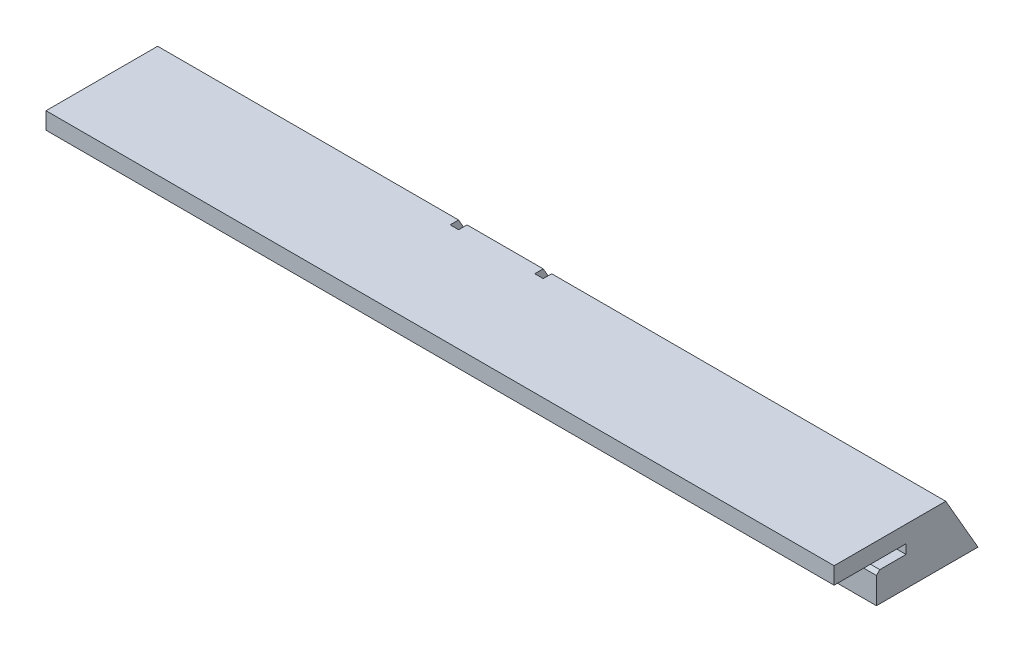
SolidWorks part; units mm, degrees
ref_plane "前视基准面" through (0, 0, 0) normal (0, 0, 1) x (1, 0, 0)
ref_plane "上视基准面" through (0, 0, 0) normal (0, 1, 0) x (1, 0, 0)
ref_plane "右视基准面" through (0, 0, 0) normal (1, 0, 0) x (0, 0, -1)
other "Configuration Table"
sketch "草图2" plane through (0, 0, 0) normal (0, 1, 0) x (1, 0, 0)
  line L1 (0, 0) -> (93.1, 0)
  line L2 (0, 0) -> (0, 10)
  line L3 (0, 10) -> (93.1, 10)
  line L4 (93.1, 0) -> (93.1, 10)
  dimension "D1" = 93.1
  dimension "D2" = 10
extrude "凸台-拉伸1" add sketch "草图2" along normal blind 3.5
sketch "草图4" plane through (0, 3.5, 0) normal (0, 1, 0) x (1, 0, 0)
  line L0 (93.1, 0) -> (93.1, 10) construction
  line L1 (0, 10) -> (93.1, 10)
  line L2 (0, 10) -> (0, 3.5)
  line L3 (0, 3.5) -> (93.1, 3.5)
  line L4 (93.1, 10) -> (93.1, 3.5)
  dimension "D1" = 6.5
extrude "凸台-拉伸2" add sketch "草图4" along normal blind 1.1
sketch "草图5" plane through (0, 4.6, 0) normal (0, 1, 0) x (1, 0, 0)
  line L0 (93.1, 3.5) -> (93.1, 10) construction
  line L1 (0, 10) -> (93.1, 10)
  line L2 (0, 10) -> (0, 0)
  line L3 (0, 0) -> (93.1, 0)
  line L4 (93.1, 10) -> (93.1, 0)
  dimension "D1" = 10
extrude "凸台-拉伸3" add sketch "草图5" along normal blind 2
sketch "草图6" plane through (0, 0, 0) normal (-1, 0, 0) x (0, 0, 1)
  line L0 (-10, 0) -> (-6.1895, 6.6)
  line L1 (-10, 0) -> (0, 0) construction
  line L2 (-10, 6.6) -> (-10, 0) construction
  line L3 (-10, 6.6) -> (0, 6.6) construction
  line L4 (-6.1895, 6.6) -> (-10, 6.6)
  line L5 (-10, 6.6) -> (-10, 0)
  dimension "D1" = 30
extrude "切除-拉伸1" cut sketch "草图6" against normal through all
sketch "草图7" plane through (0, 0, -3.5) normal (0, 0, 1) x (1, 0, 0)
  line L0 (0, 4.6) -> (93.1, 4.6) construction
  line L1 (5, 4.6) -> (88.1, 4.6)
  line L2 (5, 4.6) -> (5, 3.5)
  line L3 (5, 3.5) -> (88.1, 3.5)
  line L4 (88.1, 4.6) -> (88.1, 3.5)
  line L5 (0, 3.5) -> (93.1, 3.5) construction
  line L6 (0, 4.6) -> (0, 3.5) construction
  line L7 (93.1, 4.6) -> (93.1, 3.5) construction
  dimension "D1" = 5
  dimension "D2" = 5
extrude "凸台-拉伸4" add sketch "草图7" along normal up to surface (3.5 mm away) up to face at (46.55, 1.75, 0)
chamfer "倒角1" distance 0.4 angle 45 2 edges at (2.5, 3.5, 0) (90.6, 3.5, 0)
sketch "草图8" plane through (0, 0, 0) normal (0, -1, 0) x (1, 0, 0)
  line L0 (46.55, 147) -> (46.55, 0) construction
  line L1 (0, 0) -> (93.1, 0) construction
  line L2 (5, 0) -> (0, 0) construction
  circle A0 centre (46.55, 147) radius 150
  dimension "D1" = 300
  dimension "D2" = 147
extrude "切除-拉伸2" cut sketch "草图8" against normal up to next
sketch "草图9" plane through (0, 0, 0) normal (0, 0, 1) x (1, 0, 0)
  line L1 (0, 4.6) -> (93.1, 4.6)
  line L2 (0, 4.6) -> (0, 6.6)
  line L3 (0, 6.6) -> (93.1, 6.6)
  line L4 (93.1, 4.6) -> (93.1, 6.6)
extrude "凸台-拉伸5" add sketch "草图9" along normal blind 5 and the other way up to next
sketch "草图10" plane through (0, 4.3301, -7.5) normal (0, 0.5, -0.866) x (-1, 0, 0)
  line L4 (0, -5) -> (0, 2.621)
  line L5 (0, 2.621) -> (-93.1, 2.621)
  line L6 (-93.1, 2.621) -> (-93.1, -5)
  line L7 (-93.1, -5) -> (0, -5)
  line L8 (0, -5) -> (0, 2.621)
  line L9 (0, 2.621) -> (-93.1, 2.621)
  line L10 (-93.1, 2.621) -> (-93.1, -5)
  line L11 (-93.1, -5) -> (0, -5)
  dimension "D1" = 0
extrude "凸台-拉伸6" add sketch "草图10" along direction (0, 0, -1) on the side of the normal blind 2
sketch "草图11" plane through (0, 5.1962, -9) normal (0, 0.5, -0.866) x (-1, 0, 0)
  line L0 (0, 1.621) -> (-93.1, 1.621) construction
  line L1 (-46.55, 1.621) -> (-45.55, 1.621)
  line L2 (-46.55, 1.621) -> (-46.55, -6)
  line L3 (-46.55, -6) -> (-45.55, -6)
  line L4 (-45.55, 1.621) -> (-45.55, -6)
  line L5 (-93.1, -6) -> (0, -6) construction
  line L6 (-36.55, 1.621) -> (-36.55, -6)
  line L7 (-36.55, 1.621) -> (-35.55, 1.621)
  line L8 (-35.55, 1.621) -> (-35.55, -6)
  line L9 (-36.55, -6) -> (-35.55, -6)
  dimension "D1" = 1
  dimension "D2" = 2
  dimension "D3" = 9
extrude "切除-拉伸3" cut sketch "草图11" along direction (0, 0, 1) on the side against the normal blind 1
